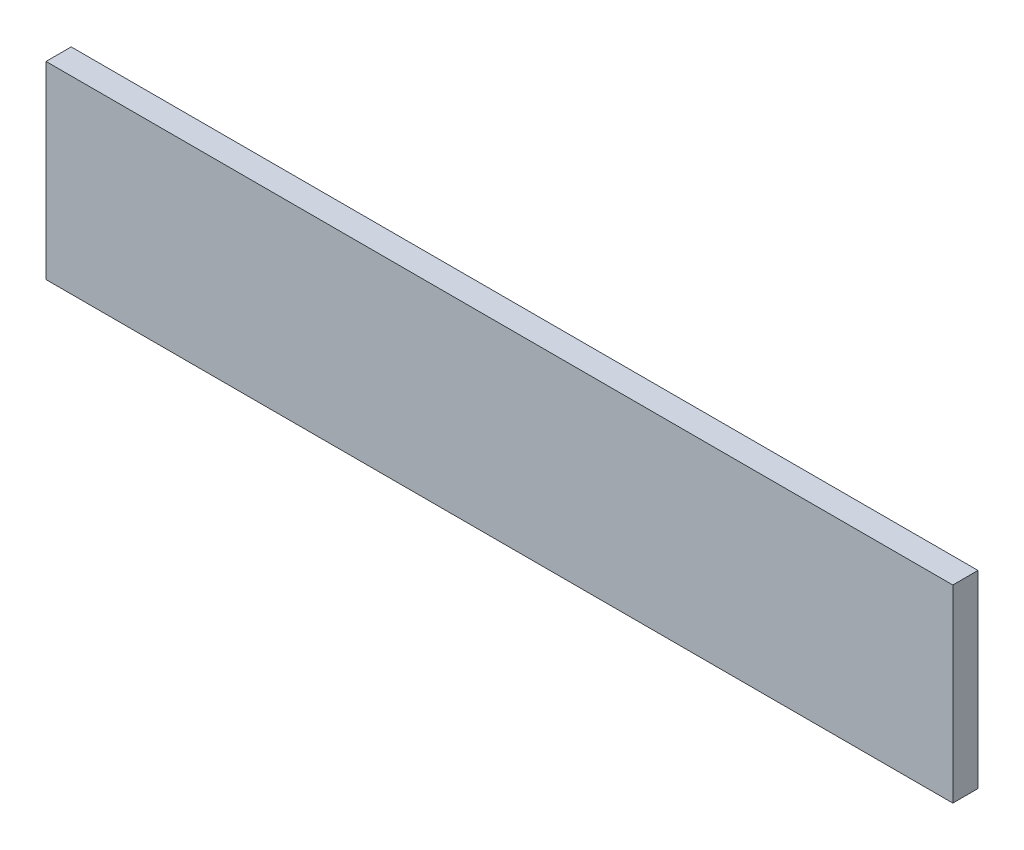
SolidWorks part; units mm, degrees
ref_plane "Front Plane" through (0, 0, 0) normal (0, 0, 1) x (1, 0, 0)
ref_plane "Top Plane" through (0, 0, 0) normal (0, 1, 0) x (1, 0, 0)
ref_plane "Right Plane" through (0, 0, 0) normal (1, 0, 0) x (0, 0, -1)
sketch "Sketch1" plane through (0, 0, 0) normal (0, 0, 1) x (1, 0, 0)
  line L1 (-36, -7.5) -> (36, -7.5)
  line L2 (-36, -7.5) -> (-36, 7.5)
  line L3 (-36, 7.5) -> (36, 7.5)
  line L4 (36, -7.5) -> (36, 7.5)
  line L5 (-36, -7.5) -> (36, 7.5) construction
  line L6 (-36, 7.5) -> (36, -7.5) construction
  point P0 (0, 0)
  dimension "D1" = 72
  dimension "D2" = 15
extrude "Boss-Extrude1" add sketch "Sketch1" along normal blind 2
